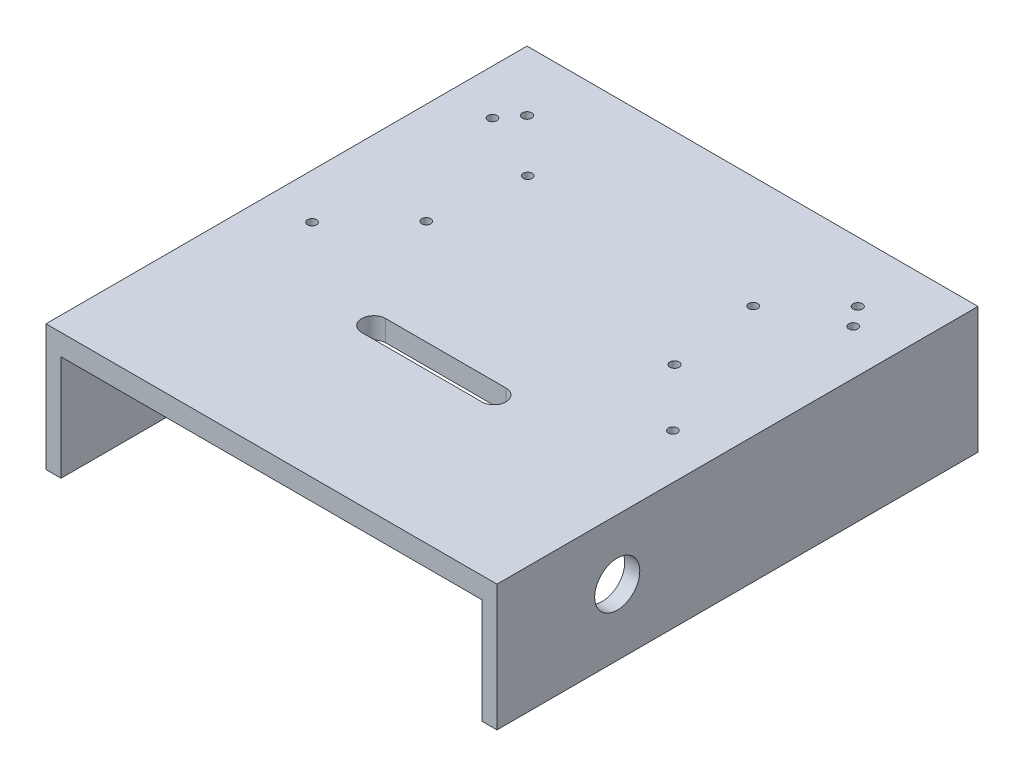
SolidWorks part; units mm, degrees
ref_plane "Front Plane" through (0, 0, 0) normal (0, 0, 1) x (1, 0, 0)
ref_plane "Top Plane" through (0, 0, 0) normal (0, 1, 0) x (1, 0, 0)
ref_plane "Right Plane" through (0, 0, 0) normal (1, 0, 0) x (0, 0, -1)
sketch "Sketch1" plane through (0, 0, 0) normal (0, 0, 1) x (1, 0, 0)
  line L0 (-95.0617, -14.5514) -> (-95.0617, 27.4486)
  line L1 (-95.0617, 27.4486) -> (54.9383, 27.4486)
  line L2 (54.9383, 27.4486) -> (54.9383, -14.5514)
  line L3 (54.9383, -14.5514) -> (49.9383, -14.5514)
  line L4 (49.9383, -14.5514) -> (49.9383, 20.4486)
  line L5 (49.9383, 20.4486) -> (-90.0617, 20.4486)
  line L6 (-90.0617, 20.4486) -> (-90.0617, -14.5514)
  line L7 (-90.0617, -14.5514) -> (-95.0617, -14.5514)
  dimension "D1" = 150
  dimension "D2" = 5
  dimension "D3" = 5
  dimension "D4" = 42
  dimension "D5" = 42
  dimension "D6" = 35
  dimension "D7" = 35
  dimension "D8" = 7
extrude "Boss-Extrude1" add sketch "Sketch1" along normal blind 160
sketch "Sketch2" plane through (0, 0, 0) normal (0, 0, -1) x (-1, 0, 0)
  line L0 (-52.4383, 15.4486) -> (-52.4383, -4.5514) construction
  line L1 (-50.9383, 15.4486) -> (-50.9383, -4.5514)
  line L2 (-53.9383, 15.4486) -> (-53.9383, -4.5514)
  line L3 (-4.9383, 23.9486) -> (45.0617, 23.9486) construction
  line L4 (-4.9383, 25.4486) -> (45.0617, 25.4486)
  line L5 (-4.9383, 22.4486) -> (45.0617, 22.4486)
  line L6 (92.5617, 15.4486) -> (92.5617, -4.5514) construction
  line L7 (94.0617, 15.4486) -> (94.0617, -4.5514)
  line L8 (91.0617, 15.4486) -> (91.0617, -4.5514)
  line L9 (-54.9383, 27.4486) -> (95.0617, 27.4486) construction
  line L12 (90.0617, 20.4486) -> (-49.9383, 20.4486) construction
  line L13 (-54.9383, -14.5514) -> (-54.9383, 27.4486) construction
  line L14 (-49.9383, 20.4486) -> (-49.9383, -14.5514) construction
  line L15 (90.0617, -14.5514) -> (90.0617, 20.4486) construction
  arc A0 (-50.9383, 15.4486) -> (-53.9383, 15.4486) centre (-52.4383, 15.4486) ccw
  arc A1 (-53.9383, -4.5514) -> (-50.9383, -4.5514) centre (-52.4383, -4.5514) ccw
  arc A2 (-4.9383, 25.4486) -> (-4.9383, 22.4486) centre (-4.9383, 23.9486) ccw
  arc A3 (45.0617, 22.4486) -> (45.0617, 25.4486) centre (45.0617, 23.9486) ccw
  arc A4 (94.0617, 15.4486) -> (91.0617, 15.4486) centre (92.5617, 15.4486) ccw
  arc A5 (91.0617, -4.5514) -> (94.0617, -4.5514) centre (92.5617, -4.5514) ccw
  point P2 (-52.4383, 5.4486)
  point P7 (20.0617, 23.9486)
  point P14 (92.5617, 5.4486)
  dimension "D1" = 22
  dimension "D2" = 3
  dimension "D3" = 20
  dimension "D4" = 2.5
  dimension "D5" = 3
  dimension "D6" = 20
  dimension "D7" = 2.5
  dimension "D8" = 22
  dimension "D9" = 3.5
  dimension "D10" = 3
  dimension "D11" = 50
  dimension "D12" = 75
extrude "Cut-Extrude1" cut sketch "Sketch2" against normal blind 32
sketch "Sketch3" plane through (-95.0617, 0, 0) normal (-1, 0, 0) x (0, 0, 1)
  line L0 (0, 27.4486) -> (0, -14.5514) construction
  line L3 (160, 27.4486) -> (0, 27.4486) construction
  circle A0 centre (120, 7.4486) radius 7.5
  dimension "D1" = 15
  dimension "D3" = 20
  dimension "D2" = 120
extrude "Cut-Extrude2" cut sketch "Sketch3" against normal blind 210
sketch "Sketch5" plane through (0, 27.4486, 0) normal (0, 1, 0) x (1, 0, 0)
  line L0 (54.9383, 0) -> (-95.0617, 0) construction
  line L1 (-95.0617, -160) -> (-95.0617, 0) construction
  line L2 (54.9383, -160) -> (54.9383, 0) construction
  circle A0 centre (-80.0617, -26.5) radius 1.5
  circle A1 centre (39.9383, -26.5) radius 1.5
  circle A2 centre (-80.0617, -86.5) radius 1.5
  circle A3 centre (39.9383, -86.5) radius 1.5
  dimension "D1" = 3
  dimension "D2" = 3
  dimension "D7" = 3
  dimension "D8" = 3
  dimension "D3" = 26.5
  dimension "D4" = 15
  dimension "D5" = 15
  dimension "D6" = 26.5
  dimension "D9" = 60
  dimension "D10" = 60
  dimension "D11" = 15
  dimension "D12" = 15
extrude "Cut-Extrude4" cut sketch "Sketch5" against normal blind 210
sketch "Sketch7" plane through (0, 27.4486, 0) normal (0, 1, 0) x (1, 0, 0)
  line L0 (-40.0617, -106) -> (-0.0617, -106) construction
  line L1 (-40.0617, -102) -> (-0.0617, -102)
  line L2 (-40.0617, -110) -> (-0.0617, -110)
  line L3 (-95.0617, -160) -> (-95.0617, 0) construction
  line L4 (54.9383, -160) -> (-95.0617, -160) construction
  arc A0 (-40.0617, -102) -> (-40.0617, -110) centre (-40.0617, -106) ccw
  arc A1 (-0.0617, -110) -> (-0.0617, -102) centre (-0.0617, -106) ccw
  point P2 (-20.0617, -106)
  dimension "D1" = 40
  dimension "D2" = 75
  dimension "D3" = 8
  dimension "D4" = 50
extrude "Cut-Extrude6" cut sketch "Sketch7" against normal blind 20
ref_plane "Plane5" through (-20.0617, 0, 0) normal (-1, 0, 0) x (0, 0, 1)
sketch "Sketch8" plane through (0, 27.4486, 0) normal (0, 1, 0) x (1, 0, 0)
  line L0 (54.9383, 0) -> (-95.0617, 0) construction
  line L1 (54.9383, -160) -> (54.9383, 0) construction
  line L2 (-95.0617, -160) -> (-95.0617, 0) construction
  circle A0 centre (-75.0617, -20) radius 1.55
  circle A1 centre (34.9383, -20) radius 1.55
  dimension "D1" = 3.1
  dimension "D2" = 3.1
  dimension "D3" = 20
  dimension "D4" = 20
  dimension "D5" = 20
  dimension "D6" = 20
extrude "Cut-Extrude7" cut sketch "Sketch8" against normal blind 10
sketch "Sketch9" plane through (0, 20.4486, 0) normal (0, -1, 0) x (1, 0, 0)
  line L0 (49.9383, 106) -> (25.9383, 106)
  line L1 (49.9383, 160) -> (49.9383, 0) construction
  line L2 (25.9383, 106) -> (25.9383, 94)
  line L3 (25.9383, 94) -> (49.9383, 94)
  line L4 (49.9383, 94) -> (49.9383, 106)
  line L5 (-90.0617, 160) -> (49.9383, 160) construction
  dimension "D1" = 24
  dimension "D2" = 12
  dimension "D3" = 54
extrude "Boss-Extrude3" add sketch "Sketch9" along normal blind 2
sketch "Sketch10" plane through (0, 18.4486, 0) normal (0, -1, 0) x (1, 0, 0)
  line L0 (25.9383, 106) -> (28.9383, 106)
  line L1 (49.9383, 106) -> (25.9383, 106) construction
  line L2 (28.9383, 106) -> (28.9383, 94)
  line L3 (25.9383, 94) -> (49.9383, 94) construction
  line L4 (28.9383, 94) -> (25.9383, 94)
  line L5 (25.9383, 94) -> (25.9383, 106)
  dimension "D1" = 3
extrude "Boss-Extrude4" add sketch "Sketch10" along normal blind 25
sketch "Sketch11" plane through (25.9383, 0, 0) normal (-1, 0, 0) x (0, 0, 1)
  line L0 (106, -6.5514) -> (94, -6.5514) construction
  line L1 (106, -6.5514) -> (106, 20.4486) construction
  circle A0 centre (100, 15.9486) radius 3.5
  circle A1 centre (100, -2.0514) radius 3.5
  dimension "D1" = 7
  dimension "D2" = 7
  dimension "D4" = 4.5
  dimension "D3" = 18
  dimension "D5" = 6
  dimension "D6" = 6
extrude "Cut-Extrude8" cut sketch "Sketch11" against normal blind 1
sketch "Sketch12" plane through (26.9383, 0, 0) normal (-1, 0, 0) x (0, 0, 1)
  circle A0 centre (100, 15.9486) radius 1.55
  circle A1 centre (100, -2.0514) radius 1.55
  dimension "D1" = 3.1
  dimension "D2" = 3.1
extrude "Cut-Extrude9" cut sketch "Sketch12" against normal blind 3
mirror "Mirror1" about plane through (-20.0617, 0, 0) normal (-1, 0, 0) of "Cut-Extrude8", "Boss-Extrude4", "Boss-Extrude3", "Cut-Extrude9"
sketch "Sketch13" plane through (0, 27.4486, 0) normal (0, 1, 0) x (1, 0, 0)
  line L0 (-95.0617, -160) -> (-95.0617, 0) construction
  line L1 (54.9383, -160) -> (54.9383, 0) construction
  circle A0 centre (17.4383, -37.2658) radius 1.5
  circle A1 centre (-57.5617, -37.2658) radius 1.5
  circle A2 centre (-61.3417, -67.2238) radius 1.5
  circle A3 centre (21.2183, -67.2238) radius 1.55
  dimension "D1" = 3
  dimension "D2" = 3
  dimension "D3" = 3
  dimension "D4" = 3.1
  dimension "D5" = 75
  dimension "D6" = 37.5
  dimension "D7" = 37.5
  dimension "D8" = 82.56
  dimension "D9" = 33.72
  dimension "D10" = 33.72
extrude "Cut-Extrude10" cut sketch "Sketch13" against normal blind 10
sketch "Sketch14" plane through (0, 20.4486, 0) normal (0, -1, 0) x (1, 0, 0)
  line L0 (2.1394, 81.6504) -> (2.1394, 56.6504) construction
  line L1 (5.1394, 81.6504) -> (5.1394, 56.6504)
  line L2 (-0.8606, 81.6504) -> (-0.8606, 56.6504)
  line L3 (-39.8606, 81.6504) -> (-39.8606, 56.6504) construction
  line L4 (-36.8606, 81.6504) -> (-36.8606, 56.6504)
  line L5 (-42.8606, 81.6504) -> (-42.8606, 56.6504)
  arc A0 (5.1394, 81.6504) -> (-0.8606, 81.6504) centre (2.1394, 81.6504) ccw
  arc A1 (-0.8606, 56.6504) -> (5.1394, 56.6504) centre (2.1394, 56.6504) ccw
  arc A2 (-36.8606, 81.6504) -> (-42.8606, 81.6504) centre (-39.8606, 81.6504) ccw
  arc A3 (-42.8606, 56.6504) -> (-36.8606, 56.6504) centre (-39.8606, 56.6504) ccw
  circle A4 centre (2.1394, 69.1504) radius 1.375
  circle A6 centre (-39.8606, 69.1504) radius 1.375
  point P2 (2.1394, 69.1504)
  point P7 (-39.8606, 69.1504)
  dimension "D5" = 2.75
  dimension "D6" = 2.75
  dimension "D1" = 6
  dimension "D2" = 6
  dimension "D3" = 25
  dimension "D4" = 25
  dimension "D7" = 42
extrude "Boss-Extrude5" add sketch "Sketch14" along normal blind 5
